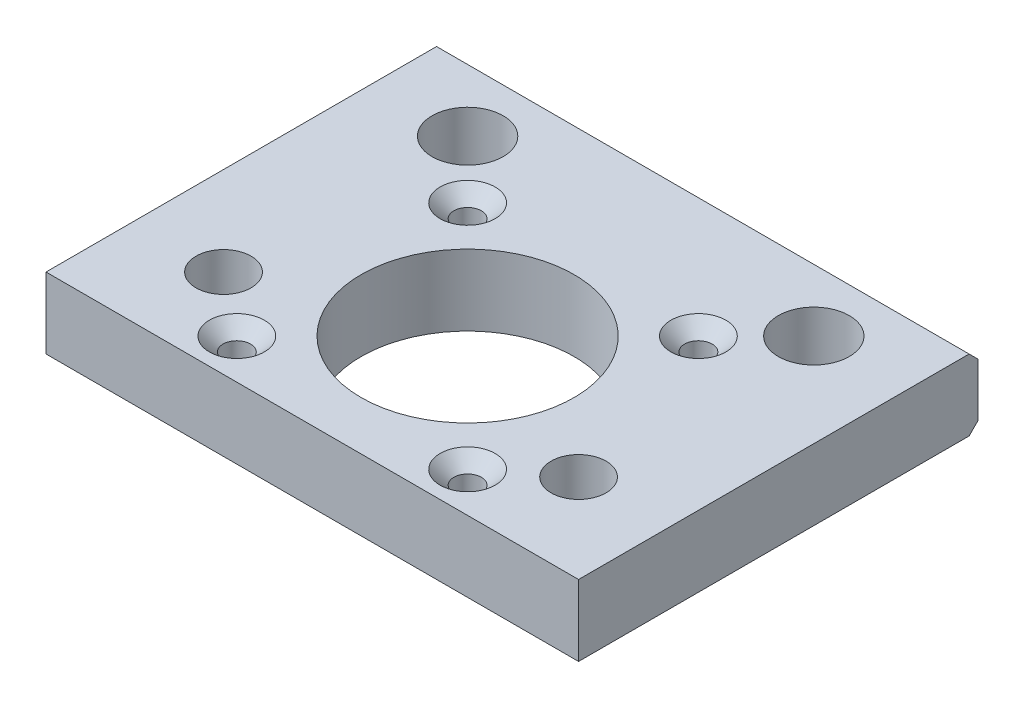
SolidWorks part; units mm, degrees
ref_plane "前视基准面" through (0, 0, 0) normal (0, 0, 1) x (1, 0, 0)
ref_plane "上视基准面" through (0, 0, 0) normal (0, 1, 0) x (1, 0, 0)
ref_plane "右视基准面" through (0, 0, 0) normal (1, 0, 0) x (0, 0, -1)
sketch "草图1" plane through (0, 0, 0) normal (0, 1, 0) x (1, 0, 0)
  line L0 (0, -55) -> (0, 55) construction
  line L1 (-30, 22.5) -> (30, 22.5)
  line L2 (-30, 22.5) -> (-30, -22.5)
  line L3 (-30, -22.5) -> (30, -22.5)
  line L4 (30, 22.5) -> (30, -22.5)
  circle A0 centre (-20, -12.5) radius 2.5
  circle A1 centre (20, -12.5) radius 2.5
  circle A2 centre (0, -5) radius 12
  point P4 (0, 22.5)
  point P5 (30, 0)
  dimension "D3" = 5
  dimension "D6" = 24
  dimension "D1" = 60
  dimension "D2" = 45
  dimension "D4" = 10
  dimension "D5" = 10
  dimension "D9" = 17.5
extrude "凸台-拉伸1" add sketch "草图1" along normal blind 8
chamfer "倒角1" distance 1 angle 45 4 edges at (30, 4, -22.5) (0, 8, -22.5) (-30, 4, -22.5) (0, 0, -22.5)
sketch "草图2" plane through (0, 8, 0) normal (0, 1, 0) x (1, 0, 0)
  line L0 (-30, 21.5) -> (-30, -22.5) construction
  line L1 (-30, -22.5) -> (30, -22.5) construction
  line L2 (0, -4.4) -> (0, 4.4) construction
  circle A0 centre (-19.5, 14.5) radius 4
  circle A1 centre (19.5, 14.5) radius 4
  dimension "D1" = 10.5
  dimension "D3" = 8
  dimension "D2" = 37
extrude "切除-拉伸1" cut sketch "草图2" against normal blind 6
sketch "草图3" plane through (0, 0, 0) normal (0, -1, 0) x (-1, 0, 0)
  line L0 (0, 4.4) -> (0, -4.4) construction
  line L1 (30, -22.5) -> (-30, -22.5) construction
  line L2 (0, 11.541) -> (0, -21.541) construction
  circle A0 centre (13, -18) radius 1.25
  circle A2 centre (-13, -18) radius 1.25
  circle A3 centre (13, 8) radius 1.25
  circle A4 centre (-13, 8) radius 1.25
  circle A8 centre (0, -5) radius 12 construction
  circle A9 centre (0, -5) radius 12 construction
  point P23 (0, -5)
  dimension "D1" = 26
  dimension "D2" = 2.5
  dimension "D3" = 4.5
  dimension "D5" = 26
  dimension "D4" = 2
extrude "切除-拉伸2" cut sketch "草图3" against normal through all
hole_wizard "打孔尺寸(%根据十字)槽半沉头木螺钉的类型2" positions "3D草图1" profile "草图4" countersink size "M6" standard "GB" end condition through all
sketch3d "3D草图1"
  line L0 (20, 8, 12.5) -> (20, 0, 12.5) construction
  line L1 (-20, 8, 12.5) -> (-20, 0, 12.5) construction
  point P0 (20, 0, 12.5)
  point P4 (-20, 0, 12.5)
sketch "草图4" plane through (20, 0, 12.5) normal (1, 0, 0) x (0, 0, -1)
  line L0 (0, 0) -> (0, 8)
  line L1 (0, 8) -> (3.1, 8)
  line L2 (3.1, 8) -> (3.1, 3.5)
  line L3 (3.1, 3.5) -> (6.6, 0)
  line L5 (6.6, 0) -> (0, 0)
  line L6 (-3.1, 3.5) -> (-6.6, 0) construction
  line L11 (0, -6.35) -> (0, 107.95) construction
  dimension "通孔孔直径" = 6.2
  dimension "通孔孔深度" = 8
  dimension "近端锥形沉头孔直径" = 13.2
  dimension "近端锥形沉头孔角度" = 90
hole_wizard "打孔尺寸(%根据十字)槽半沉头木螺钉的类型2" positions "3D草图2" profile "草图5" countersink size "M3" standard "GB" end condition through all
sketch3d "3D草图2"
  line L0 (-13, 8, -8) -> (-13, 0, -8) construction
  line L1 (-13, 8, 18) -> (-13, 0, 18) construction
  line L2 (13, 8, 18) -> (13, 0, 18) construction
  line L3 (13, 8, -8) -> (13, 0, -8) construction
  point P0 (-13, 8, -8)
  point P4 (-13, 8, 18)
  point P8 (13, 8, 18)
  point P12 (13, 8, -8)
  point P25 (-21, 8, 5)
  point P26 (0, 0, 0)
sketch "草图5" plane through (-13, 8, -8) normal (1, 0, 0) x (0, 0, 1)
  line L0 (0, 0) -> (0, 8)
  line L1 (0, 8) -> (1.55, 8)
  line L2 (1.55, 8) -> (1.55, 1.55)
  line L3 (1.55, 1.55) -> (3.1, 0)
  line L5 (3.1, 0) -> (0, 0)
  line L6 (-1.55, 1.55) -> (-3.1, 0) construction
  line L11 (0, -6.35) -> (0, 107.95) construction
  dimension "通孔孔直径" = 3.1
  dimension "通孔孔深度" = 8
  dimension "近端锥形沉头孔直径" = 6.2
  dimension "近端锥形沉头孔角度" = 90
